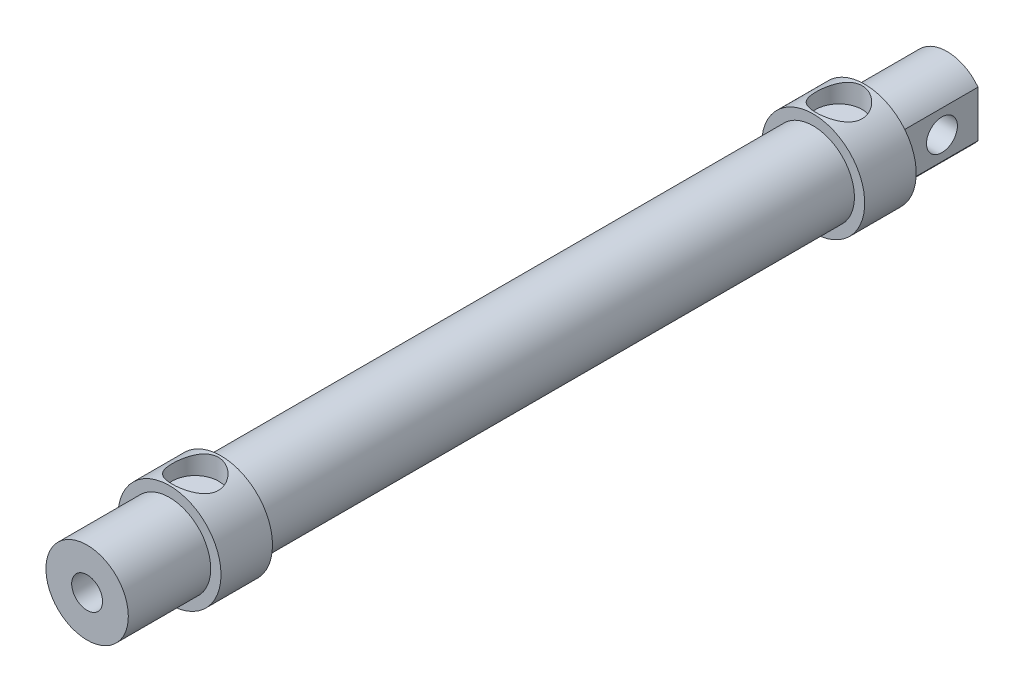
SolidWorks part; units mm, degrees
ref_plane "Front Plane" through (0, 0, 0) normal (0, 0, 1) x (1, 0, 0)
ref_plane "Top Plane" through (0, 0, 0) normal (0, 1, 0) x (1, 0, 0)
ref_plane "Right Plane" through (0, 0, 0) normal (1, 0, 0) x (0, 0, -1)
sketch "Sketch1" plane through (0, 0, 0) normal (0, 0, 1) x (1, 0, 0)
  circle A0 centre (0, 0) radius 8
extrude "Boss-Extrude1" add sketch "Sketch1" along normal blind 115
sketch "Sketch2" plane through (0, 0, 0) normal (0, 0, -1) x (-1, 0, 0)
  circle A0 centre (0, 0) radius 10
extrude "Boss-Extrude2" add sketch "Sketch2" along normal blind 10
sketch "Sketch3" plane through (0, 0, 115) normal (0, 0, 1) x (1, 0, 0)
  circle A0 centre (0, 0) radius 10
extrude "Boss-Extrude3" add sketch "Sketch3" along normal blind 10
sketch "Sketch4" plane through (0, 0, 125) normal (0, 0, 1) x (1, 0, 0)
  circle A0 centre (0, 0) radius 8
extrude "Boss-Extrude4" add sketch "Sketch4" along normal blind 16
sketch "Sketch5" plane through (0, 0, -10) normal (0, 0, -1) x (-1, 0, 0)
  circle A0 centre (0, 0) radius 7.5
extrude "Boss-Extrude5" add sketch "Sketch5" along normal blind 16
sketch "Sketch6" plane through (0, 0, 141) normal (0, 0, 1) x (1, 0, 0)
  circle A0 centre (0, 0) radius 3
extrude "Cut-Extrude1" cut sketch "Sketch6" against normal blind 75
ref_plane "Plane3" through (0, 10, 0) normal (0, 1, 0) x (-1, 0, 0)
sketch "Sketch7" plane through (0, 10, 0) normal (0, 1, 0) x (-1, 0, 0)
  line L0 (10, 125) -> (-10, 125) construction
  line L1 (-8, 115) -> (8, 115) construction
  line L2 (10, 0) -> (-10, 0) construction
  line L3 (-10, -10) -> (10, -10) construction
  line L4 (10, 125) -> (-10, 125) construction
  line L5 (-8, 115) -> (8, 115) construction
  line L6 (10, 0) -> (-10, 0) construction
  line L7 (-10, -10) -> (10, -10) construction
  line L8 (0, 125) -> (0, 115) construction
  line L9 (0, 0) -> (0, -10) construction
  circle A0 centre (0, 120) radius 4.5
  circle A1 centre (0, -5) radius 4.5
extrude "Cut-Extrude2" cut sketch "Sketch7" against normal blind 4
sketch "Sketch8" plane through (0, 0, -26) normal (0, 0, -1) x (-1, 0, 0)
  line L0 (0, 7.5) -> (0, -7.5) construction
  line L1 (-6, 4.5) -> (-6, -4.5)
  line L2 (6, 4.5) -> (6, -4.5)
  line L3 (-10, 0) -> (10, 0) construction
  line L4 (-6, 7.5) -> (-6, -7.5) construction
  line L5 (6, 7.5) -> (6, -7.5) construction
  circle A0 centre (0, 0) radius 7.5 construction
  circle A1 centre (0, 0) radius 7.5
  arc A2 (-6, 4.5) -> (-6, -4.5) centre (0, 0) ccw
  circle A3 centre (0, 0) radius 7.5 construction
  arc A4 (6, -4.5) -> (6, 4.5) centre (0, 0) ccw
  circle A5 centre (0, 0) radius 10 construction
  dimension "D2" = 6
  dimension "D1" = 0
  dimension "D3" = 6
extrude "Cut-Extrude3" cut sketch "Sketch8" against normal up to surface (16 mm away) up to face at (-10, 0, -10)
sketch "Sketch9" plane through (6, 0, 0) normal (1, 0, 0) x (0, 0, -1)
  line L0 (26, -4.5) -> (26, 4.5) construction
  circle A0 centre (19, 0) radius 3
  dimension "D1" = 7
extrude "Cut-Extrude4" cut sketch "Sketch9" against normal through all
